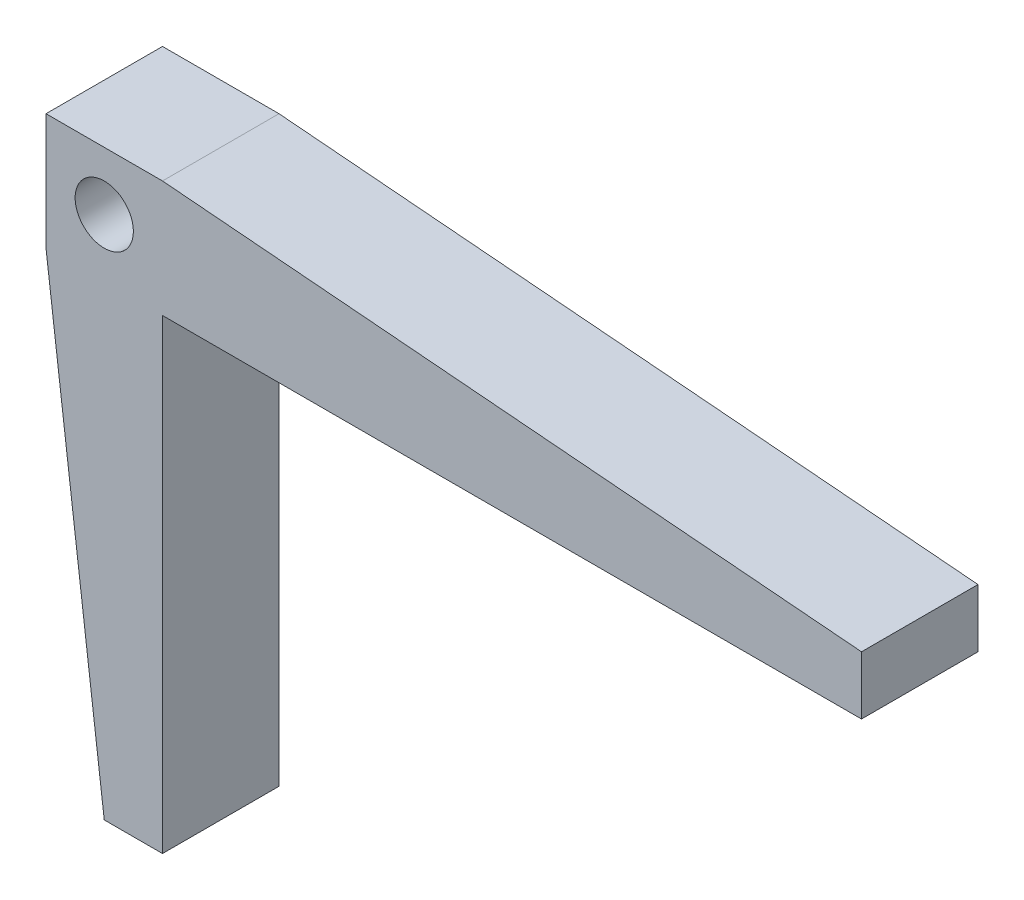
SolidWorks part; units mm, degrees
ref_plane "Front Plane" through (0, 0, 0) normal (0, 0, 1) x (1, 0, 0)
ref_plane "Top Plane" through (0, 0, 0) normal (0, 1, 0) x (1, 0, 0)
ref_plane "Right Plane" through (0, 0, 0) normal (1, 0, 0) x (0, 0, -1)
sketch "Sketch1" plane through (0, 0, 0) normal (0, 0, 1) x (1, 0, 0)
  line L0 (0, 0) -> (0, -101.6)
  line L1 (0, -101.6) -> (-12.7, -101.6)
  line L2 (-12.7, -101.6) -> (-25.4, 0)
  line L3 (-25.4, 0) -> (-25.4, 25.4)
  line L4 (-25.4, 25.4) -> (0, 25.4)
  line L5 (0, 25.4) -> (152.4, 12.7)
  line L6 (152.4, 12.7) -> (152.4, 0)
  line L7 (152.4, 0) -> (0, 0)
  circle A0 centre (-12.7, 12.7) radius 6.35
  point P3 (0, 0)
  point P12 (-25.4, 12.7)
  point P13 (-12.7, 12.7)
  point P14 (-12.7, 25.4)
  dimension "D7" = 12.7
  dimension "D1" = 152.4
  dimension "D2" = 101.6
  dimension "D3" = 12.7
  dimension "D4" = 12.7
  dimension "D5" = 25.4
  dimension "D6" = 25.4
extrude "Boss-Extrude1" add sketch "Sketch1" along normal blind 25.4
